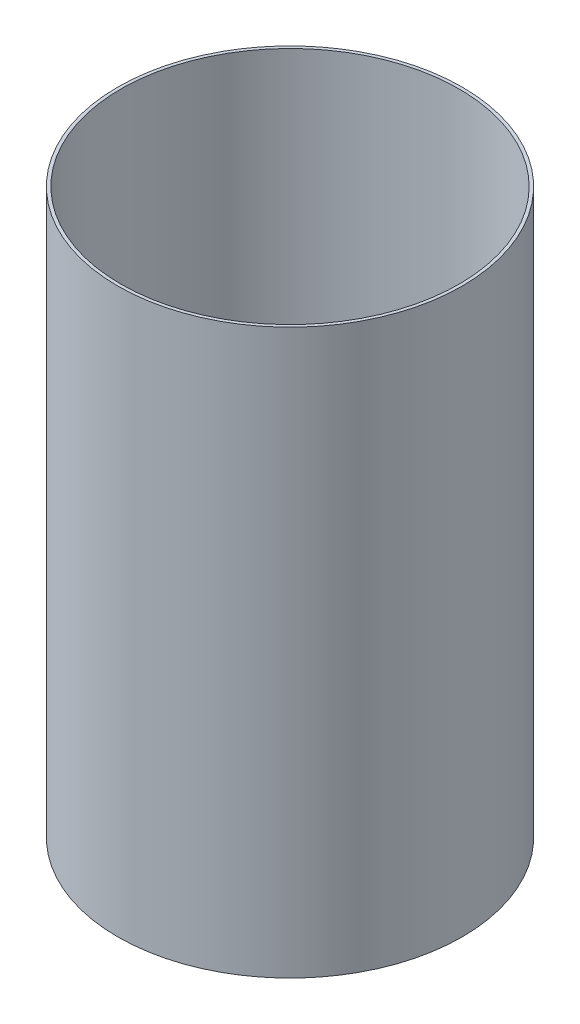
SolidWorks part; units mm, degrees
material "Thornel Mat VMA"
ref_plane "Front Plane" through (0, 0, 0) normal (0, 0, 1) x (1, 0, 0)
ref_plane "Top Plane" through (0, 0, 0) normal (0, 1, 0) x (1, 0, 0)
ref_plane "Right Plane" through (0, 0, 0) normal (1, 0, 0) x (0, 0, -1)
sketch "Sketch1" plane through (0, 0, 0) normal (0, 1, 0) x (1, 0, 0)
  circle A0 centre (0, 0) radius 77.6224
  circle A1 centre (0, 0) radius 76.2
  dimension "D1" = 152.4
  dimension "D2" = 155.2448
extrude "Boss-Extrude1" add sketch "Sketch1" along normal blind 254
equation "\"airframeInnerDiameter\"= 6in"
equation "\"outerDiameter\"= 6.112in"
equation "\"airframeBulkheadThickness\"= 0.125in"
equation "\"payloadAirframeLength\"= 10in"
equation "\"payloadInnerDiameter\"= 6in - 0.056in"
equation "\"payloadOuterDiameter\"= \"airframeInnerDiameter\""
equation "\"payloadLength\"= 11in"
equation "\"recoveryCouplerOuter\"=\"airframeInnerDiameter\""
equation "\"atsCouplerOuter\"=\"airframeInnerDiameter\""
equation "\"D1@Sketch1\"=\"airframeInnerDiameter\""
equation "\"D2@Sketch1\"=\"outerDiameter\""
equation "\"D1@Boss-Extrude1\"=\"payloadAirframeLength\""
